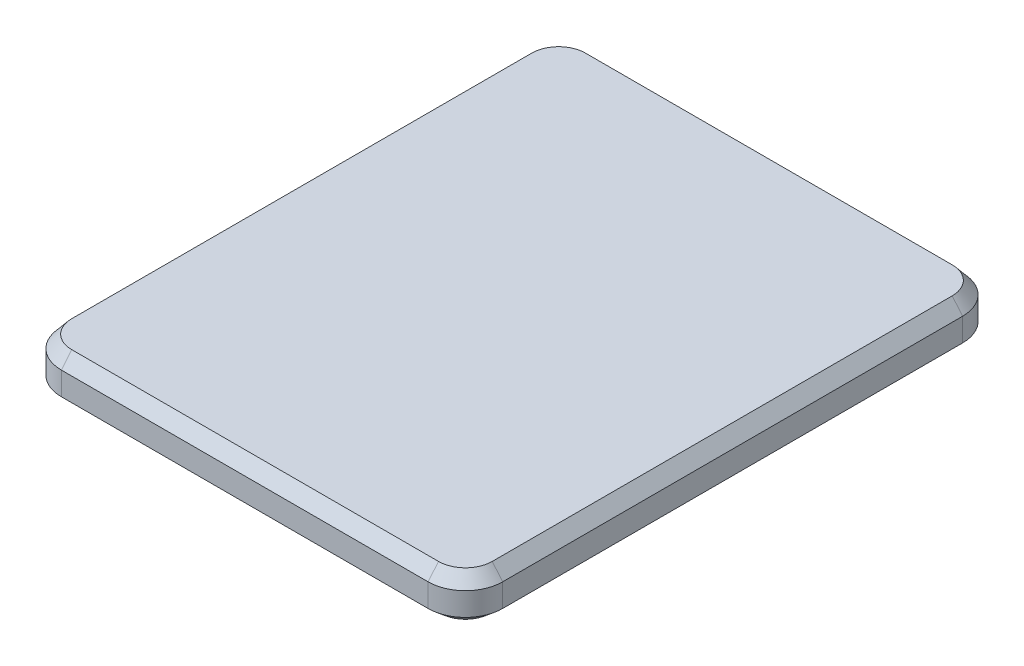
SolidWorks part; units mm, degrees
ref_plane "Спереди" through (0, 0, 0) normal (0, 0, 1) x (1, 0, 0)
ref_plane "Сверху" through (0, 0, 0) normal (0, 1, 0) x (1, 0, 0)
ref_plane "Справа" through (0, 0, 0) normal (1, 0, 0) x (0, 0, -1)
sketch "Эскиз1" plane through (0, 0, 0) normal (0, 1, 0) x (1, 0, 0)
  line L1 (-17.75, 21.5) -> (17.75, 21.5)
  line L2 (-17.75, 21.5) -> (-17.75, -21.5)
  line L3 (-17.75, -21.5) -> (17.75, -21.5)
  line L4 (17.75, 21.5) -> (17.75, -21.5)
  line L5 (-17.75, 21.5) -> (17.75, -21.5) construction
  line L6 (-17.75, -21.5) -> (17.75, 21.5) construction
  point P0 (0, 0)
  dimension "D1" = 43
  dimension "D2" = 35.5
extrude "Бобышка-Вытянуть1" add sketch "Эскиз1" along normal blind 3.7
fillet "Скругление1" radius 3 4 edges at (-17.75, 1.85, -21.5) (17.75, 1.85, -21.5) (17.75, 1.85, 21.5) (-17.75, 1.85, 21.5)
chamfer "Фаска1" distance 1 angle 40 16 edges at (-16.8713, 0, 20.6213) (0, 0, 21.5) (16.8713, 0, 20.6213) (17.75, 0, 0) (16.8713, 0, -20.6213) (0, 0, -21.5) (-16.8713, 0, -20.6213) (-17.75, 0, 0) (16.8713, 3.7, -20.6213) (17.75, 3.7, 0) (16.8713, 3.7, 20.6213) (0, 3.7, 21.5) (-16.8713, 3.7, 20.6213) (-17.75, 3.7, 0) (-16.8713, 3.7, -20.6213) (0, 3.7, -21.5)
